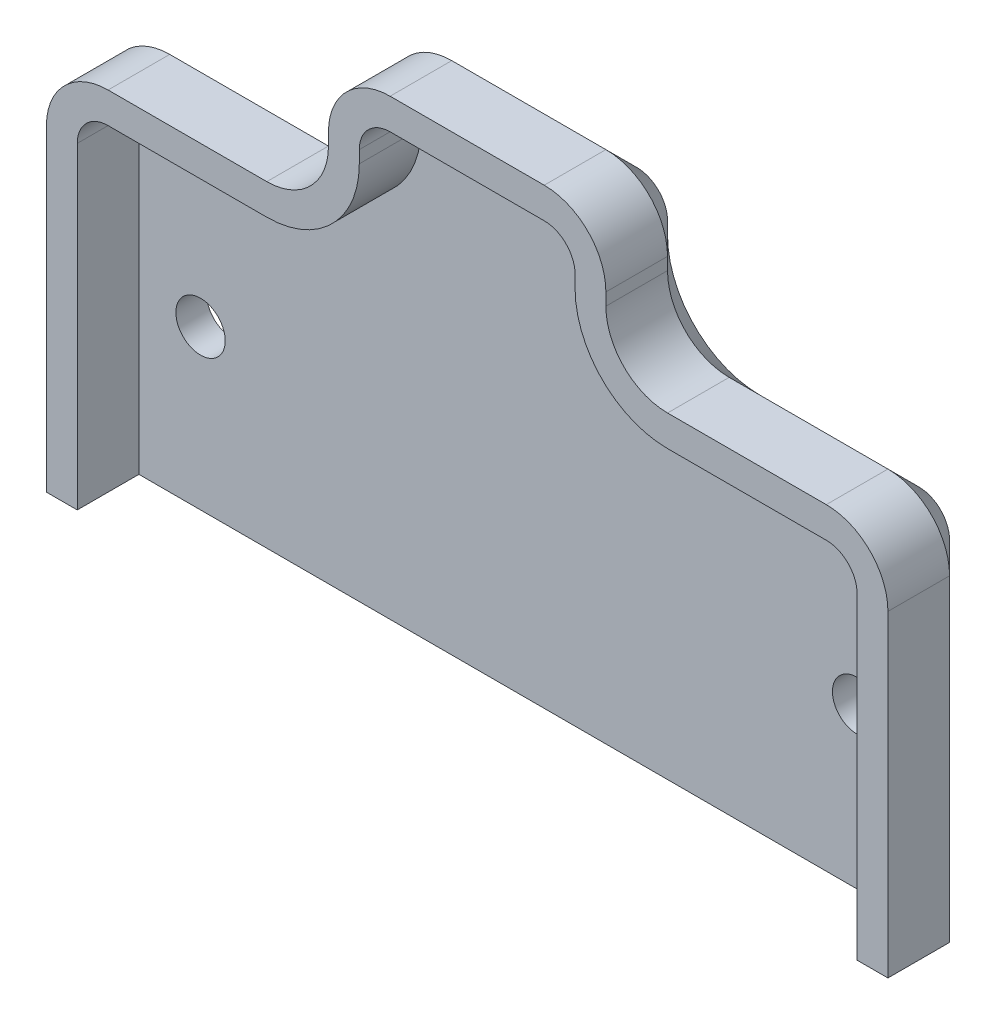
SolidWorks part; units mm, degrees
ref_plane "Front Plane" through (0, 0, 0) normal (0, 0, 1) x (1, 0, 0)
ref_plane "Top Plane" through (0, 0, 0) normal (0, 1, 0) x (1, 0, 0)
ref_plane "Right Plane" through (0, 0, 0) normal (1, 0, 0) x (0, 0, -1)
sketch "Sketch1" plane through (0, 0, 0) normal (0, 0, 1) x (1, 0, 0)
  line L0 (26.8163, 5.1921) -> (35.9663, 5.1921)
  line L1 (8.6663, -7.1079) -> (35.9663, -7.1079)
  line L2 (8.6663, -7.1079) -> (8.6663, 5.1921)
  line L3 (8.6663, 5.1921) -> (17.8163, 5.1921)
  line L4 (35.9663, -7.1079) -> (35.9663, 5.1921)
  line L6 (17.8163, 5.1921) -> (17.8163, 9.5921)
  line L7 (17.8163, 9.5921) -> (26.8163, 9.5921)
  line L8 (26.8163, 5.1921) -> (26.8163, 9.5921)
  line L13 (14.6663, -11.1079) -> (29.9663, -11.1079) construction
  line L14 (19.8163, 3.1921) -> (16.6663, 3.1921) construction
  line L16 (19.8163, 7.8921) -> (19.8163, 3.1921) construction
  line L17 (24.8163, 3.1921) -> (24.8163, 7.8921) construction
  circle A0 centre (11.6663, -1.9579) radius 0.7 construction
  dimension "D4" = 3
  dimension "D1" = 4.4
  dimension "D2" = 2
  dimension "D3" = 2
  dimension "D5" = 4
  dimension "D6" = 2
extrude "Boss-Extrude1" add sketch "Sketch1" along normal blind 1
sketch "Sketch2" plane through (0, 0, 1) normal (0, 0, 1) x (1, 0, 0)
  line L0 (34.9663, -7.1079) -> (34.9663, 4.1921)
  line L1 (34.9663, 4.1921) -> (25.8163, 4.1921)
  line L2 (25.8163, 4.1921) -> (25.8163, 8.5921)
  line L3 (25.8163, 8.5921) -> (18.8163, 8.5921)
  line L4 (18.8163, 8.5921) -> (18.8163, 4.1921)
  line L5 (18.8163, 4.1921) -> (9.6663, 4.1921)
  line L6 (9.6663, 4.1921) -> (9.6663, -7.1079)
  line L7 (8.6663, -7.1079) -> (9.6663, -7.1079)
  line L8 (8.6663, 5.1921) -> (8.6663, -7.1079)
  line L9 (8.6663, -7.1079) -> (35.9663, -7.1079)
  line L10 (35.9663, -7.1079) -> (35.9663, 5.1921)
  line L11 (35.9663, 5.1921) -> (26.8163, 5.1921)
  line L12 (26.8163, 5.1921) -> (26.8163, 9.5921)
  line L13 (26.8163, 9.5921) -> (17.8163, 9.5921)
  line L14 (17.8163, 9.5921) -> (17.8163, 5.1921)
  line L15 (17.8163, 5.1921) -> (8.6663, 5.1921)
  line L16 (8.6663, 5.1921) -> (8.6663, -7.1079)
  line L18 (35.9663, -7.1079) -> (35.9663, 5.1921)
  line L19 (35.9663, 5.1921) -> (26.8163, 5.1921)
  line L20 (26.8163, 5.1921) -> (26.8163, 9.5921)
  line L21 (26.8163, 9.5921) -> (17.8163, 9.5921)
  line L22 (17.8163, 9.5921) -> (17.8163, 5.1921)
  line L23 (17.8163, 5.1921) -> (8.6663, 5.1921)
  line L24 (34.9663, -7.1079) -> (35.9663, -7.1079)
  dimension "D1" = 0
  dimension "D2" = 1
extrude "Boss-Extrude2" add sketch "Sketch2" along normal blind 2
fillet "Fillet1" radius 1 4 edges at (34.9663, 4.1921, 2) (9.6663, 4.1921, 2) (25.8163, 8.5921, 2) (18.8163, 8.5921, 2)
fillet "Fillet2" radius 2 6 edges at (8.6663, 5.1921, 1.5) (35.9663, 5.1921, 1.5) (17.8163, 9.5921, 1.5) (26.8163, 9.5921, 1.5) (26.8163, 5.1921, 1.5) (17.8163, 5.1921, 1.5)
fillet "Fillet3" radius 3 2 edges at (25.8163, 4.1921, 2) (18.8163, 4.1921, 2)
sketch "Sketch3" plane through (0, 0, 0) normal (0, 0, -1) x (-1, 0, 0)
  line L0 (-22.3163, 9.5921) -> (-22.3163, -7.1079) construction
  line L1 (-24.8163, 9.5921) -> (-19.8163, 9.5921) construction
  line L2 (-8.6663, -7.1079) -> (-35.9663, -7.1079) construction
  circle A0 centre (-32.9663, -1.9579) radius 0.8
  circle A1 centre (-11.6663, -1.9579) radius 0.8
  dimension "D1" = 1.6
extrude "Cut-Extrude1" cut sketch "Sketch3" against normal through all
chamfer "Chamfer1" distance 1 angle 45 13 edges at (35.9663, -1.9579, 0) (8.6663, -1.9579, 0) (35.3805, 4.6063, 0) (9.2521, 4.6063, 0) (31.3913, 5.1921, 0) (13.2413, 5.1921, 0) (27.4021, 5.7779, 0) (17.2305, 5.7779, 0) (26.8163, 7.3921, 0) (17.8163, 7.3921, 0) (26.2305, 9.0063, 0) (18.4021, 9.0063, 0) (22.3163, 9.5921, 0)
